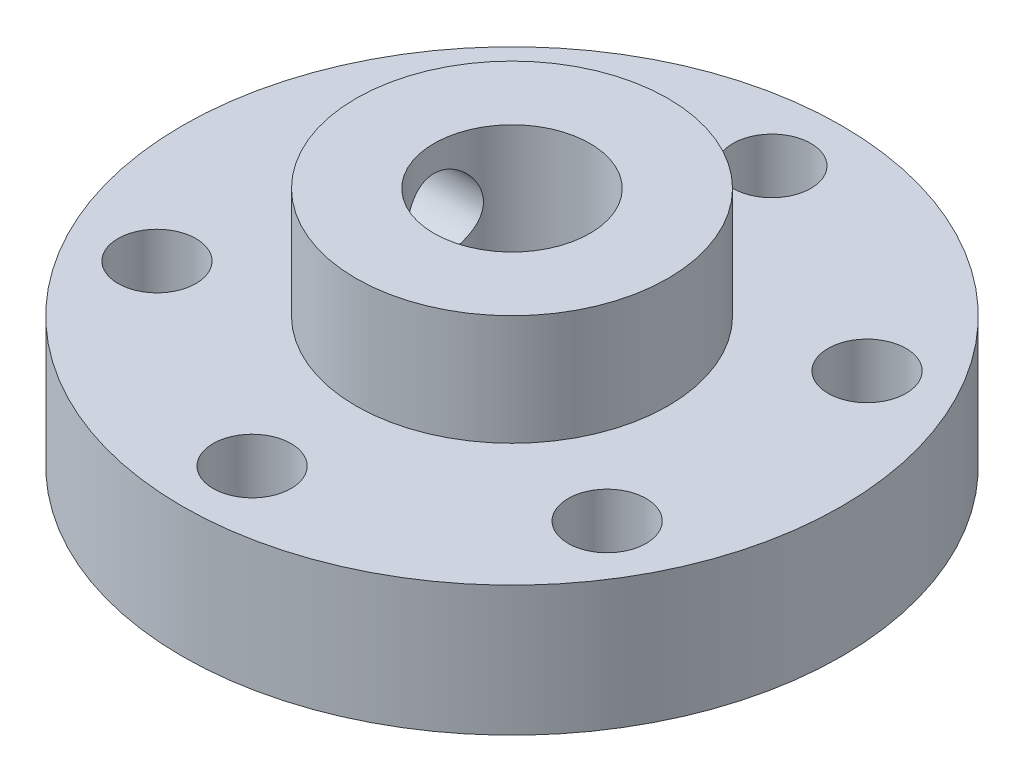
SolidWorks part; units mm, degrees
ref_plane "Front Plane" through (0, 0, 0) normal (0, 0, 1) x (1, 0, 0)
ref_plane "Top Plane" through (0, 0, 0) normal (0, 1, 0) x (1, 0, 0)
ref_plane "Right Plane" through (0, 0, 0) normal (1, 0, 0) x (0, 0, -1)
sketch "Sketch1" plane through (0, 0, 0) normal (0, 1, 0) x (1, 0, 0)
  circle A0 centre (0, 0) radius 12.685
  circle A1 centre (0, 0) radius 3
  dimension "D1" = 25.37
  dimension "D2" = 6
extrude "Boss-Extrude1" add sketch "Sketch1" along normal blind 5
sketch "Sketch2" plane through (0, 0, 0) normal (0, 1, 0) x (1, 0, 0)
  circle A0 centre (0, 0) radius 3
  circle A1 centre (0, 0) radius 6
  dimension "D1" = 6
  dimension "D2" = 12
extrude "Boss-Extrude2" add sketch "Sketch2" along normal blind 9.25
sketch "Sketch3" plane through (0, 0, 0) normal (0, 1, 0) x (1, 0, 0)
  line L0 (0, -6.6) -> (0, 6.6) construction
  circle A0 centre (0, 10) radius 1.5
  circle A1 centre (8.6603, 5) radius 1.5
  circle A2 centre (8.6603, -5) radius 1.5
  circle A3 centre (0, -10) radius 1.5
  circle A4 centre (-8.6603, -5) radius 1.5
  circle A5 centre (-8.6603, 5) radius 1.5
  point P14 (0, 0)
  point P18 (0, 0)
  dimension "D1" = 3
  dimension "D2" = 10
  dimension "D3" = 6
extrude "Cut-Extrude1" cut sketch "Sketch3" along normal blind 12
sketch "Sketch5" plane through (0, 0, 0) normal (1, 0, 0) x (0, -1, 0)
  line L0 (-9.25, 6) -> (-9.25, -6) construction
  line L1 (-5.0875, 0) -> (5.0875, 0) construction
  line L2 (0, 13.9535) -> (0, -13.9535) construction
  circle A0 centre (-6.75, 0) radius 1.5
  circle A1 centre (-2.5, 0) radius 1.5
  dimension "D2" = 3
  dimension "D3" = 3
  dimension "D1" = 2.5
  dimension "D4" = 2.5
extrude "Cut-Extrude3" cut sketch "Sketch5" against normal through all
